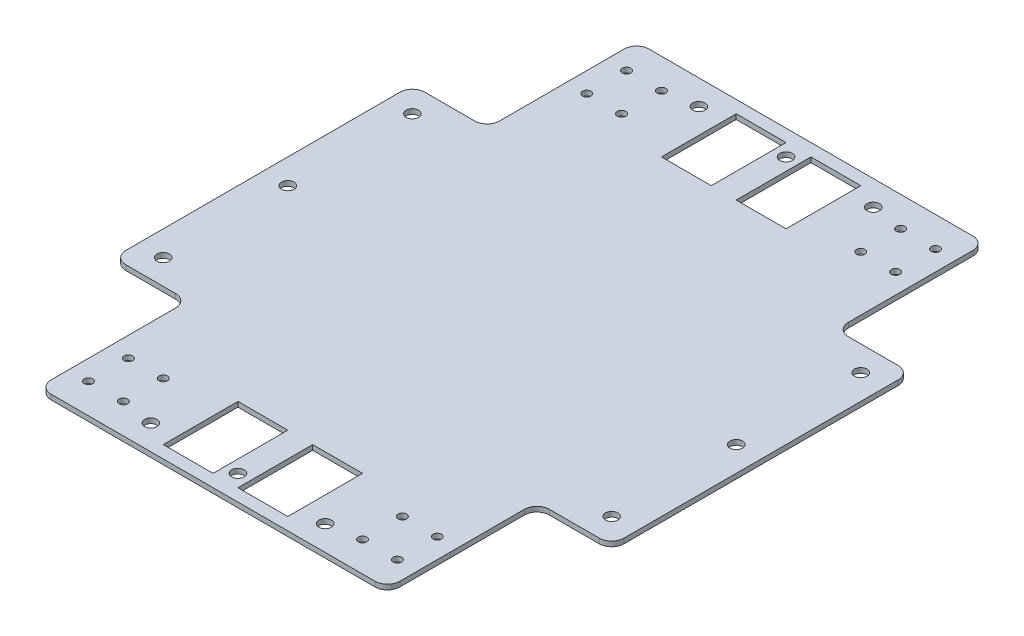
SolidWorks part; units mm, degrees
ref_plane "前视基准面" through (0, 0, 0) normal (0, 0, 1) x (1, 0, 0)
ref_plane "上视基准面" through (0, 0, 0) normal (0, 1, 0) x (1, 0, 0)
ref_plane "右视基准面" through (0, 0, 0) normal (1, 0, 0) x (0, 0, -1)
other "Configuration Table"
sketch "草图1" plane through (0, 0, 0) normal (0, 1, 0) x (1, 0, 0)
  line L0 (0, 120) -> (0, -49880) construction
  line L5 (-100, -120) -> (100, 120) construction
  line L6 (-100, 120) -> (100, -120) construction
  line L7 (-100, 120) -> (-70, 120)
  line L8 (-100, 120) -> (-100, 80)
  line L9 (-95, 80) -> (-75, 80)
  line L10 (-70, 115) -> (-70, 85)
  line L11 (-65, 0) -> (49935, 0) construction
  line L12 (-70, 120) -> (-70, 113)
  line L13 (-70, 113) -> (-70, 87)
  line L14 (-70, 87) -> (-70, 80)
  line L15 (-70, 113) -> (-40, 113)
  line L16 (-40, 113) -> (-40, 87)
  line L17 (-40, 87) -> (-70, 87)
  line L18 (-70, 113) -> (-70, 108)
  line L19 (-70, 87) -> (-70, 92)
  line L20 (-40, 87) -> (-48, 87)
  line L21 (-48, 87) -> (-48, 92)
  line L22 (-48, 92) -> (-40, 92)
  line L23 (-70, 92) -> (-62, 92)
  line L24 (-62, 92) -> (-62, 87)
  line L25 (-70, 100) -> (-40, 100) construction
  line L26 (0, 120) -> (0, 0)
  line L27 (0, 0) -> (-100, 0)
  line L28 (-70, 80) -> (0, 80)
  line L29 (95, 80) -> (75, 80)
  line L30 (70, 115) -> (70, 85)
  line L31 (95, -80) -> (75, -80)
  line L32 (70, -115) -> (70, -85)
  line L33 (-70, -115) -> (-70, -85)
  line L34 (-95, -80) -> (-75, -80)
  line L35 (0, 120) -> (0, 100)
  line L36 (0, 100) -> (-25, 100)
  line L37 (-25, 100) -> (-25, 115)
  line L38 (-25, 100) -> (-25, 85)
  line L39 (-25, 85) -> (-5, 85)
  line L40 (-25, 115) -> (-5, 115)
  line L41 (-5, 115) -> (-5, 85)
  line L42 (5, 115) -> (5, 85)
  line L43 (25, 100) -> (25, 85)
  line L44 (25, 85) -> (5, 85)
  line L45 (25, 115) -> (5, 115)
  line L46 (25, 100) -> (25, 115)
  line L47 (25, -85) -> (5, -85)
  line L48 (25, -100) -> (25, -85)
  line L49 (25, -100) -> (25, -115)
  line L50 (25, -115) -> (5, -115)
  line L51 (5, -115) -> (5, -85)
  line L52 (-25, -100) -> (-25, -115)
  line L53 (-25, -100) -> (-25, -85)
  line L54 (-25, -85) -> (-5, -85)
  line L55 (-5, -115) -> (-5, -85)
  line L56 (-25, -115) -> (-5, -115)
  line L57 (-100, 0) -> (-90, 0)
  line L58 (0, 120) -> (0, 100)
  line L59 (0, 120) -> (0, 110)
  line L60 (-100, 75) -> (-100, -75)
  line L61 (-65, -120) -> (65, -120)
  line L62 (100, 75) -> (100, -75)
  line L63 (-65, 120) -> (65, 120)
  circle A0 centre (-62, 92) radius 1.7
  circle A1 centre (-48, 92) radius 1.7
  circle A2 centre (-48, 108) radius 1.7
  circle A3 centre (-62, 108) radius 1.7
  circle A4 centre (48, 108) radius 1.7
  circle A5 centre (48, 92) radius 1.7
  circle A6 centre (62, 92) radius 1.7
  circle A7 centre (62, 108) radius 1.7
  circle A8 centre (62, -108) radius 1.7
  circle A9 centre (62, -92) radius 1.7
  circle A10 centre (48, -92) radius 1.7
  circle A11 centre (48, -108) radius 1.7
  circle A12 centre (-48, -92) radius 1.7
  circle A13 centre (-62, -92) radius 1.7
  circle A14 centre (-48, -108) radius 1.7
  circle A15 centre (-62, -108) radius 1.7
  circle A16 centre (-90, 0) radius 2.5
  circle A17 centre (-90, 50) radius 2.5
  circle A18 centre (-90, -50) radius 2.5
  circle A19 centre (90, -50) radius 2.5
  circle A20 centre (90, 0) radius 2.5
  circle A21 centre (90, 50) radius 2.5
  circle A22 centre (0, 110) radius 2.5
  circle A23 centre (35, 110) radius 2.5
  circle A24 centre (-35, 110) radius 2.5
  circle A25 centre (35, -110) radius 2.5
  circle A26 centre (0, -110) radius 2.5
  circle A27 centre (-35, -110) radius 2.5
  arc A28 (-95, -80) -> (-100, -75) centre (-95, -75) cw
  arc A29 (-70, -85) -> (-75, -80) centre (-75, -85) ccw
  arc A30 (-65, -120) -> (-70, -115) centre (-65, -115) cw
  arc A31 (70, -115) -> (65, -120) centre (65, -115) cw
  arc A32 (70, 85) -> (75, 80) centre (75, 85) ccw
  arc A33 (75, -80) -> (70, -85) centre (75, -85) ccw
  arc A34 (95, -80) -> (100, -75) centre (95, -75) ccw
  arc A35 (95, 80) -> (100, 75) centre (95, 75) cw
  arc A36 (70, 115) -> (65, 120) centre (65, 115) ccw
  arc A37 (-70, 115) -> (-65, 120) centre (-65, 115) cw
  arc A38 (-70, 85) -> (-75, 80) centre (-75, 85) cw
  arc A39 (-95, 80) -> (-100, 75) centre (-95, 75) ccw
  point P0 (0, 0)
  point P15 (-100, -80)
  point P119 (-70, -80)
  point P122 (-70, -120)
  point P125 (70, -120)
  point P128 (70, 80)
  point P131 (70, -80)
  point P134 (100, -80)
  point P137 (100, 80)
  point P140 (70, 120)
  dimension "D12" = 3.4
  dimension "D13" = 3.4
  dimension "D19" = 5
  dimension "D23" = 5
  dimension "D25" = 5
  dimension "D26" = 5
  dimension "D1" = 200
  dimension "D2" = 240
  dimension "D3" = 30
  dimension "D4" = 40
  dimension "D5" = 7
  dimension "D6" = 7
  dimension "D7" = 30
  dimension "D8" = 5
  dimension "D9" = 5
  dimension "D10" = 8
  dimension "D11" = 8
  dimension "D14" = 25
  dimension "D15" = 15
  dimension "D16" = 15
  dimension "D17" = 20
  dimension "D18" = 10
  dimension "D21" = 20
  dimension "D22" = 10
  dimension "D20" = 2
  dimension "D24" = 2
extrude "凸台-拉伸6" add sketch "草图1" along normal blind 2
sketch "草图2" plane through (0, 2, 0) normal (0, 1, 0) x (1, 0, 0)
  line L0 (-100, 75) -> (-70, 75)
  line L1 (-70, 75) -> (-70, 85)
  line L2 (-70, 85) -> (-100, 85)
  line L3 (-100, 85) -> (-100, 75)
  line L4 (-100, 75) -> (-100, 60)
  line L5 (-100, 75) -> (-100, -75) construction
  line L6 (-95, 60) -> (-75, 60)
  line L7 (-70, 60) -> (-70, 75)
  line L8 (0, 120) -> (0, -49880) construction
  line L9 (-65, 120) -> (65, 120) construction
  line L10 (-100, 0) -> (49900, 0) construction
  line L11 (100, 75) -> (100, 60)
  line L12 (100, 85) -> (100, 75)
  line L13 (70, 75) -> (70, 85)
  line L14 (70, 85) -> (100, 85)
  line L15 (100, 75) -> (70, 75)
  line L16 (70, 65) -> (70, 75)
  line L17 (100, 60) -> (75, 60)
  line L18 (100, 0) -> (-49900, 0) construction
  line L19 (95, -60) -> (75, -60)
  line L20 (100, -75) -> (100, -60)
  line L21 (100, -85) -> (100, -75)
  line L22 (70, -75) -> (70, -85)
  line L23 (70, -85) -> (100, -85)
  line L24 (100, -75) -> (70, -75)
  line L25 (70, -65) -> (70, -75)
  line L26 (-70, -75) -> (-70, -85)
  line L27 (-70, -65) -> (-70, -75)
  line L28 (-95, -60) -> (-75, -60)
  line L29 (-100, -75) -> (-100, -60)
  line L30 (-100, -85) -> (-100, -75)
  line L31 (-70, -85) -> (-100, -85)
  line L32 (-100, -75) -> (-70, -75)
  line L33 (-100, 55) -> (-100, 52.4814)
  line L34 (-100, 52.4814) -> (-81.1327, 52.4814)
  line L35 (-81.1327, 52.4814) -> (-70, 52.4814)
  line L36 (-70, 52.4814) -> (-70, 60)
  line L37 (-100, -55) -> (-100, -48.4485)
  line L38 (-100, -48.4485) -> (-70, -48.4485)
  line L39 (-70, -48.4485) -> (-70, -60)
  line L40 (70, -60) -> (70, -53.021)
  line L41 (70, -53.021) -> (100, -53.021)
  line L42 (100, 75) -> (100, -75) construction
  line L43 (100, -53.021) -> (100, -55)
  line L44 (70, 60) -> (70, 52.4814)
  line L45 (70, 52.4814) -> (100, 52.4814)
  line L46 (100, 52.4814) -> (100, 55)
  line L47 (-70, 75) -> (-70, 65)
  line L48 (-100, -55) -> (-100, -60)
  line L49 (-70, -60) -> (-70, -65)
  line L50 (-100, 60) -> (-100, 55)
  line L51 (-100, 60) -> (-95, 60)
  line L52 (-70, 60) -> (-70, 65)
  line L53 (70, 60) -> (70, 65)
  line L54 (100, 60) -> (100, 55)
  line L55 (70, -60) -> (70, -65)
  line L56 (70, -65) -> (70, -60)
  line L57 (100, -60) -> (100, -53.021)
  arc A0 (-100, 55) -> (-95, 60) centre (-95, 55) cw
  arc A1 (75, 60) -> (70, 65) centre (75, 65) cw
  arc A2 (95, 60) -> (100, 55) centre (95, 55) cw
  arc A3 (95, -60) -> (100, -55) centre (95, -55) ccw
  arc A4 (70, -65) -> (75, -60) centre (75, -65) cw
  arc A5 (-75, -60) -> (-70, -65) centre (-75, -65) cw
  arc A6 (-100, -55) -> (-95, -60) centre (-95, -55) ccw
  arc A7 (-75, 60) -> (-70, 65) centre (-75, 65) ccw
  point P15 (0, 120)
  point P18 (-100, 0)
  dimension "D3" = 5
  dimension "D4" = 5
  dimension "D1" = 10
  dimension "D2" = 15
extrude "切除-拉伸2" cut sketch "草图2" against normal blind 2 contours L6 A7 L7 L0 L4 L51 | L50 A0 L51 | L2 L3 L0 L1 | L17 A2 L54 | A1 L17 L11 L15 L16 | L15 L12 L14 L13 | A4 L25 L24 L20 L57 A3 L19 | L21 L24 L22 L23 | L32 L30 L31 L26 | A6 L48 L29 L32 L27 A5 L28
